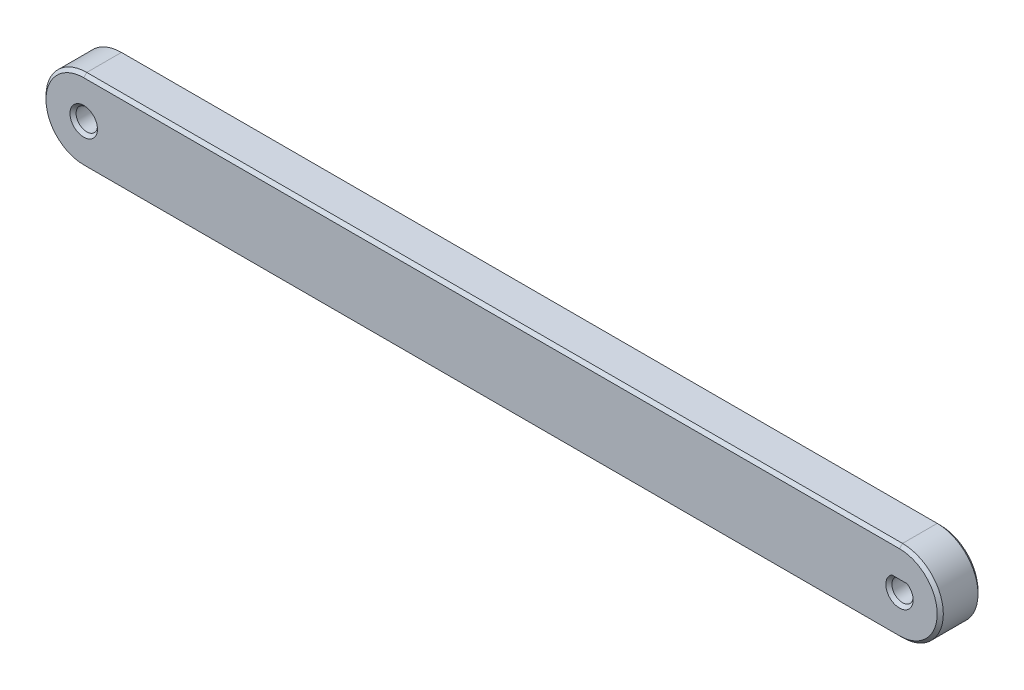
SolidWorks part; units mm, degrees
ref_plane "Front Plane" through (0, 0, 0) normal (0, 0, 1) x (1, 0, 0)
ref_plane "Top Plane" through (0, 0, 0) normal (0, 1, 0) x (1, 0, 0)
ref_plane "Right Plane" through (0, 0, 0) normal (1, 0, 0) x (0, 0, -1)
sketch "Sketch1" plane through (0, 0, 0) normal (0, 0, 1) x (1, 0, 0)
  line L0 (-100, 10) -> (100, 10)
  line L1 (-100, 10) -> (100, -10) construction
  line L2 (100, -10) -> (-100, -10)
  line L3 (98.3387, 2) -> (101.6613, 2)
  arc A0 (-100, 10) -> (-100, -10) centre (-100, 0) ccw
  arc A2 (100, 10) -> (100, -10) centre (100, 0) cw
  circle A4 centre (100, 0) radius 2.6
  circle A5 centre (-100, 0) radius 2.625
  dimension "D3" = 5.25
  dimension "D5" = 5.2
  dimension "D1" = 200
  dimension "D2" = 20
  dimension "D4" = 2
extrude "Boss-Extrude1" add sketch "Sketch1" along normal blind 10 contours L1 A0 L2 A5 | L0 L1 A2 A4 | L3 A4
sketch "Sketch2" plane through (0, 0, 0) normal (0, 0, -1) x (-1, 0, 0)
  circle A0 centre (100, 0) radius 6.5
  dimension "D1" = 13
extrude "Cut-Extrude1" cut sketch "Sketch2" against normal blind 4 contours A0
chamfer "Chamfer1" distance 0.75 angle 45 15 edges at (-97.375, 0, 10) (-102.625, 0, 4) (0, -10, 0) (0, -10, 10) (-110, 0, 0) (-110, 0, 10) (110, 0, 0) (110, 0, 10) (0, 10, 0) (0, 10, 10) (100, 2, 0) (100, -2.6, 0) (100, 2, 10) (100, -2.6, 10) (-106.5, 0, 0)
